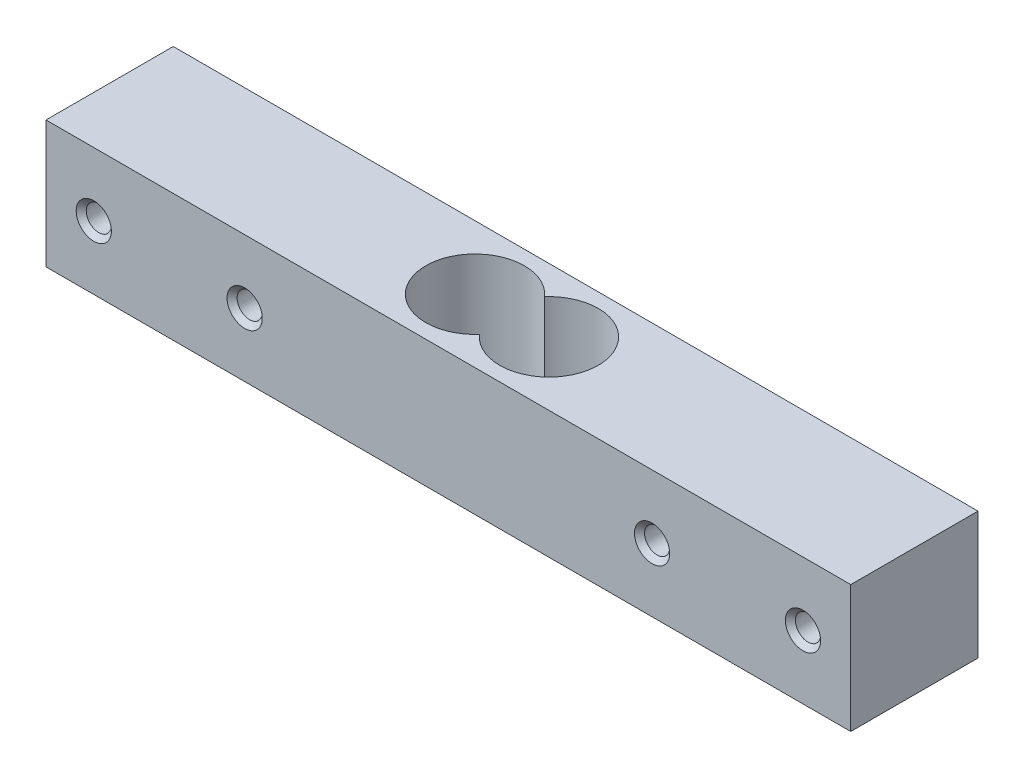
SolidWorks part; units mm, degrees
ref_plane "Front Plane" through (0, 0, 0) normal (0, 0, 1) x (1, 0, 0)
ref_plane "Top Plane" through (0, 0, 0) normal (0, 1, 0) x (1, 0, 0)
ref_plane "Right Plane" through (0, 0, 0) normal (1, 0, 0) x (0, 0, -1)
sketch "Sketch1" plane through (0, 0, 0) normal (0, 1, 0) x (1, 0, 0)
  line L0 (0, 0) -> (0, 50927.2988) construction
  line L1 (-40, -6.325) -> (40, -6.325)
  line L2 (-40, -6.325) -> (-40, 6.325)
  line L3 (-40, 6.325) -> (40, 6.325)
  line L4 (40, -6.325) -> (40, 6.325)
  line L5 (-40, -6.325) -> (40, 6.325) construction
  line L6 (-40, 6.325) -> (40, -6.325) construction
  circle A0 centre (-3.675, 0) radius 4.9
  circle A1 centre (3.675, 0) radius 4.9
  point P0 (0, 0)
  dimension "D1" = 9.8
  dimension "D2" = 12.65
  dimension "D3" = 80
  dimension "D4" = 7.35
extrude "Boss-Extrude1" add sketch "Sketch1" along normal mid plane 12.65 contours L1 L4 L3 L2 A1 A0
sketch "Sketch2" plane through (0, 0, -6.325) normal (0, 0, -1) x (-1, 0, 0)
  line L0 (-35.25, 0) -> (-20.25, 0) construction
  line L1 (-20.25, 0) -> (20.25, 0) construction
  line L2 (20.25, 0) -> (35.25, 0) construction
  point P6 (0, 0)
  dimension "D1" = 70.5
  dimension "D2" = 40.5
hole_wizard "M3 Tapped Hole1" positions "Sketch3" profile "Sketch5" tap size "M3" standard "DIN" end condition through all
sketch "Sketch3" plane through (0, 0, -6.325) normal (0, 0, -1) x (-1, 0, 0)
  point P0 (35.25, 0)
  point P3 (20.25, 0)
  point P6 (-20.25, 0)
  point P9 (-35.25, 0)
cosmetic thread "Hole Thread1" parameters "D2"=3
cosmetic thread "Hole Thread2" parameters "D2"=3
cosmetic thread "Hole Thread3" parameters "D2"=3
cosmetic thread "Hole Thread4" parameters "D2"=3
sketch "Sketch5" plane through (-35.25, 0, -6.325) normal (1, 0, 0) x (0, 1, 0)
  line L0 (0, 0) -> (0, 12.65)
  line L1 (0, 12.65) -> (1.75, 12.65)
  line L2 (1.25, 12.15) -> (1.25, 0.5)
  line L3 (1.25, 0.5) -> (1.75, 0)
  line L5 (1.75, 0) -> (0, 0)
  line L6 (-1.25, 0.5) -> (-1.75, 0) construction
  line L7 (1.75, 12.65) -> (1.25, 12.15)
  line L8 (-1.75, 12.65) -> (-1.25, 12.15) construction
  line L11 (0, -6.35) -> (0, 107.95) construction
  dimension "Thru Tap Drill Dia." = 2.5
  dimension "Thru Tap Drill Depth" = 12.65
  dimension "Near C'Sink Dia." = 3.5
  dimension "Near C'Sink Angle" = 90
  dimension "Far C'Sink Dia." = 3.5
  dimension "Far C'Sink Angle" = 90
